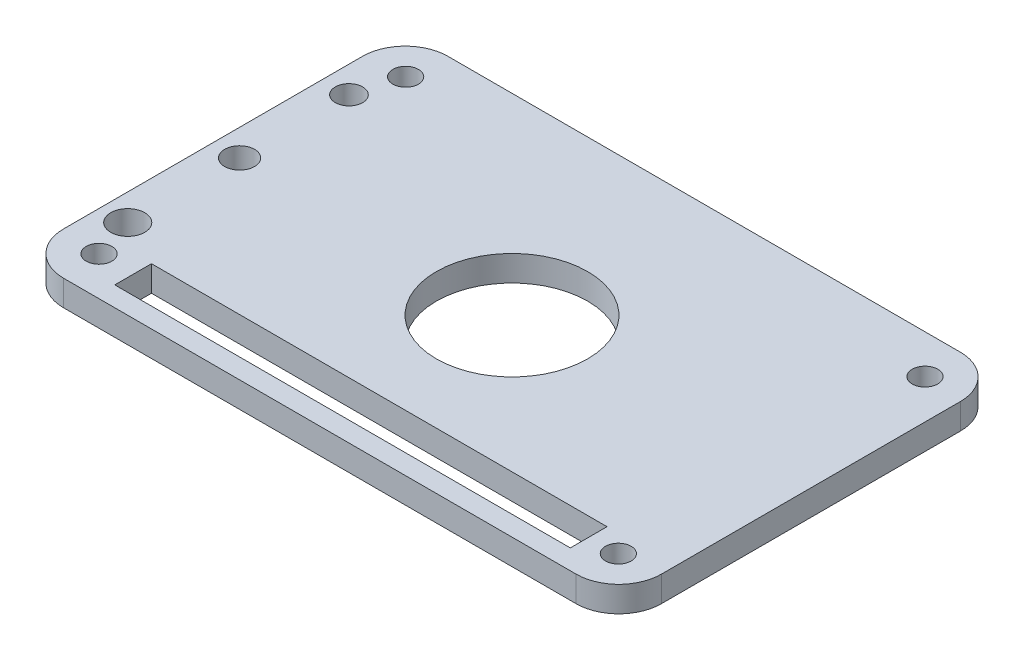
SolidWorks part; units mm, degrees
ref_plane "前视基准面" through (0, 0, 0) normal (0, 0, 1) x (1, 0, 0)
ref_plane "上视基准面" through (0, 0, 0) normal (0, 1, 0) x (1, 0, 0)
ref_plane "右视基准面" through (0, 0, 0) normal (1, 0, 0) x (0, 0, -1)
other "Configuration Table"
sketch "草图1" plane through (0, 0, 0) normal (0, 1, 0) x (1, 0, 0)
  line L0 (54.1419, 0) -> (-59.0939, 0) construction
  line L1 (-30, 22.5) -> (30, 22.5)
  line L2 (-35, 17.5) -> (-35, -17.5)
  line L3 (-30, -22.5) -> (30, -22.5)
  line L4 (35, 17.5) -> (35, -17.5)
  line L5 (-35, 22.5) -> (35, -22.5) construction
  line L6 (-35, -22.5) -> (35, 22.5) construction
  line L7 (0, 32.1795) -> (0, -44.2991) construction
  circle A0 centre (-30.4, -17.95) radius 1.5
  circle A1 centre (30.4, -17.95) radius 1.5
  circle A2 centre (30.4, 17.95) radius 1.5
  circle A3 centre (-30.4, 17.95) radius 1.5
  arc A4 (-35, -17.5) -> (-30, -22.5) centre (-30, -17.5) ccw
  arc A5 (30, -22.5) -> (35, -17.5) centre (30, -17.5) ccw
  arc A6 (30, 22.5) -> (35, 17.5) centre (30, 17.5) cw
  arc A7 (-30, 22.5) -> (-35, 17.5) centre (-30, 17.5) ccw
  point P0 (0, 0)
  dimension "D3" = 3
  dimension "D6" = 5
  dimension "D7" = 5
  dimension "D1" = 45
  dimension "D2" = 70
  dimension "D4" = 60.8
  dimension "D5" = 35.9
extrude "凸台-拉伸1" add sketch "草图1" along normal blind 3
sketch "草图2" plane through (0, 3, 0) normal (0, 1, 0) x (1, 0, 0)
  line L0 (-31.893, 17.8052) -> (-31.893, -18.0948) construction
  line L1 (27.0069, -15.8797) -> (-26.3279, -15.8797)
  line L2 (27.0069, -15.8797) -> (27.0069, -20.1797)
  line L3 (27.0069, -20.1797) -> (-26.3279, -20.1797)
  line L4 (-26.3279, -15.8797) -> (-26.3279, -20.1797)
  circle A0 centre (0, 0) radius 8.8563
  circle A1 centre (-31.893, 12.8052) radius 1.6003
  circle A2 centre (-31.893, 0) radius 1.7502
  circle A3 centre (-31.893, -13.0948) radius 1.9931
  circle A4 centre (-30.4, 17.95) radius 1.5 construction
  circle A5 centre (-30.4, -17.95) radius 1.5 construction
  dimension "D1" = 5
  dimension "D2" = 5
extrude "切除-拉伸1" cut sketch "草图2" against normal through all
